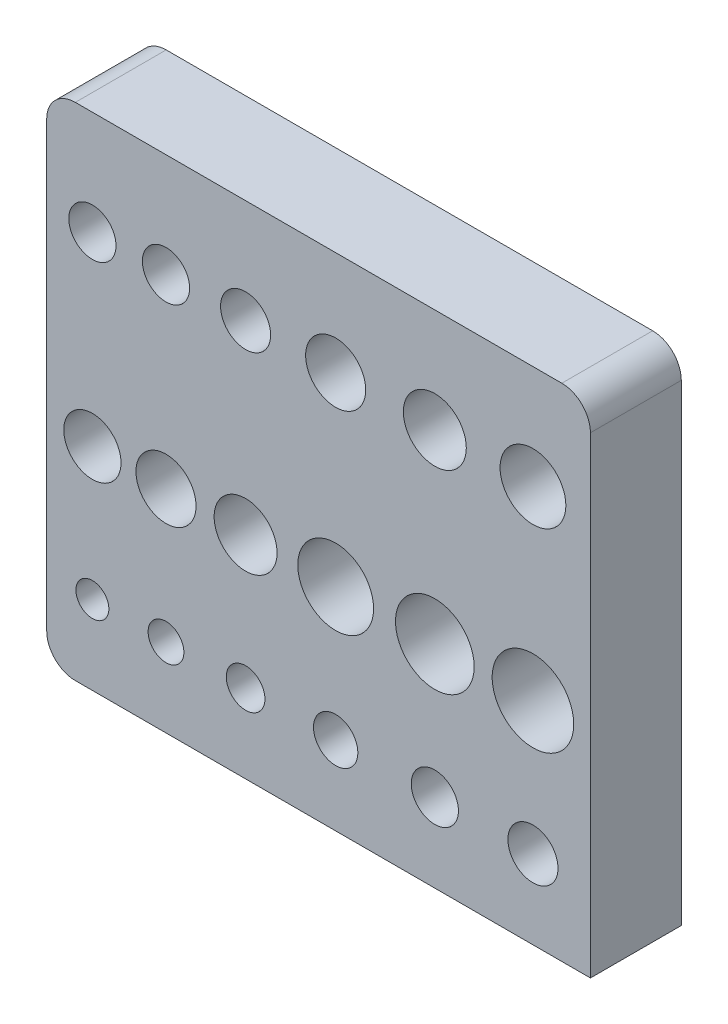
SolidWorks part; units mm, degrees
ref_plane "Front Plane" through (0, 0, 0) normal (0, 0, 1) x (1, 0, 0)
ref_plane "Top Plane" through (0, 0, 0) normal (0, 1, 0) x (1, 0, 0)
ref_plane "Right Plane" through (0, 0, 0) normal (1, 0, 0) x (0, 0, -1)
sketch "Sketch1" plane through (0, 0, 0) normal (0, 0, 1) x (1, 0, 0)
  line L1 (2, 0) -> (38, 0)
  line L2 (0, 2) -> (0, 33)
  line L3 (2, 35) -> (36, 35)
  line L4 (38, 0) -> (38, 33)
  circle A0 centre (8.3364, 27.7374) radius 1.65
  circle A1 centre (27.1246, 27.7374) radius 2.2
  circle A2 centre (8.3364, 14.775) radius 2.1
  circle A3 centre (27.1246, 14.775) radius 2.75
  circle A4 centre (13.8996, 27.7374) radius 1.75
  circle A5 centre (33.9827, 27.7374) radius 2.3
  circle A6 centre (20.1951, 27.7374) radius 2.1
  circle A7 centre (3.1928, 27.7374) radius 1.65
  circle A8 centre (33.9827, 14.775) radius 2.85
  circle A9 centre (20.1951, 14.775) radius 2.65
  circle A10 centre (3.1928, 14.775) radius 2
  circle A11 centre (13.8996, 14.775) radius 2.2
  circle A12 centre (8.3364, 5.5043) radius 1.25
  circle A13 centre (27.1246, 5.5043) radius 1.65
  circle A14 centre (13.8996, 5.5043) radius 1.35
  circle A15 centre (33.9827, 5.5043) radius 1.75
  circle A16 centre (20.1951, 5.5043) radius 1.55
  circle A17 centre (3.1928, 5.5043) radius 1.15
  arc A18 (38, 33) -> (36, 35) centre (36, 33) ccw
  arc A19 (0, 2) -> (2, 0) centre (2, 2) ccw
  arc A20 (0, 33) -> (2, 35) centre (2, 33) cw
  point P15 (12.3029, 40.7861)
  point P16 (19.4582, 40.7861)
  point P19 (17.1768, 39.2307)
  point P20 (25.7838, 40.7861)
  point P21 (18.3175, 40.7861)
  point P22 (10.7474, 40.7861)
  point P23 (4.2144, 40.7861)
  point P24 (9.2956, 40.7861)
  point P25 (15.725, 40.7861)
  point P26 (25.2653, 40.7861)
  point P27 (19.4582, 40.7861)
  point P28 (10.1252, 40.7861)
  point P31 (14.5843, 40.7861)
  point P32 (30.8651, 40.7861)
  point P33 (25.2653, 40.7861)
  point P34 (19.4582, 40.7861)
  point P35 (13.8584, 40.7861)
  point P36 (8.9845, 40.7861)
  point P39 (3.9033, 40.7861)
  point P40 (25.2653, 27.8238)
  point P43 (31.6947, 27.8238)
  point P46 (18.5249, 27.8238)
  point P51 (5.8476, 18.9056)
  point P52 (12.614, 27.8238)
  point P53 (7.3254, 27.8238)
  point P54 (2.5552, 27.8238)
  point P55 (33.9416, 27.8238)
  point P56 (27.0835, 27.8238)
  point P57 (20.154, 27.8238)
  point P58 (13.8584, 27.8238)
  point P59 (8.1523, 27.8238)
  point P60 (3.1516, 27.8238)
  point P61 (8.9845, 28.3102)
  point P62 (3.366, 23.9525)
  point P63 (8.2952, 27.8238)
  point P64 (3.1516, 27.8238)
  point P65 (3.1516, 40.7861)
  point P66 (8.2952, 40.7861)
  point P67 (13.8584, 40.7861)
  point P68 (20.154, 40.7861)
  point P69 (27.0835, 40.7861)
  point P70 (33.9416, 40.7861)
  point P83 (27.0835, 18.553)
  point P84 (33.9416, 18.553)
  point P85 (20.154, 18.553)
  point P86 (13.8584, 18.553)
  point P87 (8.2952, 18.553)
  point P88 (3.1516, 18.553)
  point P91 (38, 35)
  point P94 (0, 0)
  point P97 (0, 35)
  dimension "D3" = 3.3
  dimension "D4" = 4.4
  dimension "D5" = 4.2
  dimension "D6" = 5.5
  dimension "D7" = 3.5
  dimension "D8" = 4.6
  dimension "D9" = 4.2
  dimension "D10" = 3.3
  dimension "D11" = 5.7
  dimension "D12" = 5.3
  dimension "D13" = 4
  dimension "D14" = 4.4
  dimension "D15" = 2.3
  dimension "D16" = 2.5
  dimension "D17" = 3.3
  dimension "D18" = 3.5
  dimension "D19" = 3.1
  dimension "D20" = 2.7
  dimension "D21" = 2
  dimension "D1" = 35
  dimension "D2" = 38
extrude "Boss-Extrude1" add sketch "Sketch1" along normal blind 6.35
